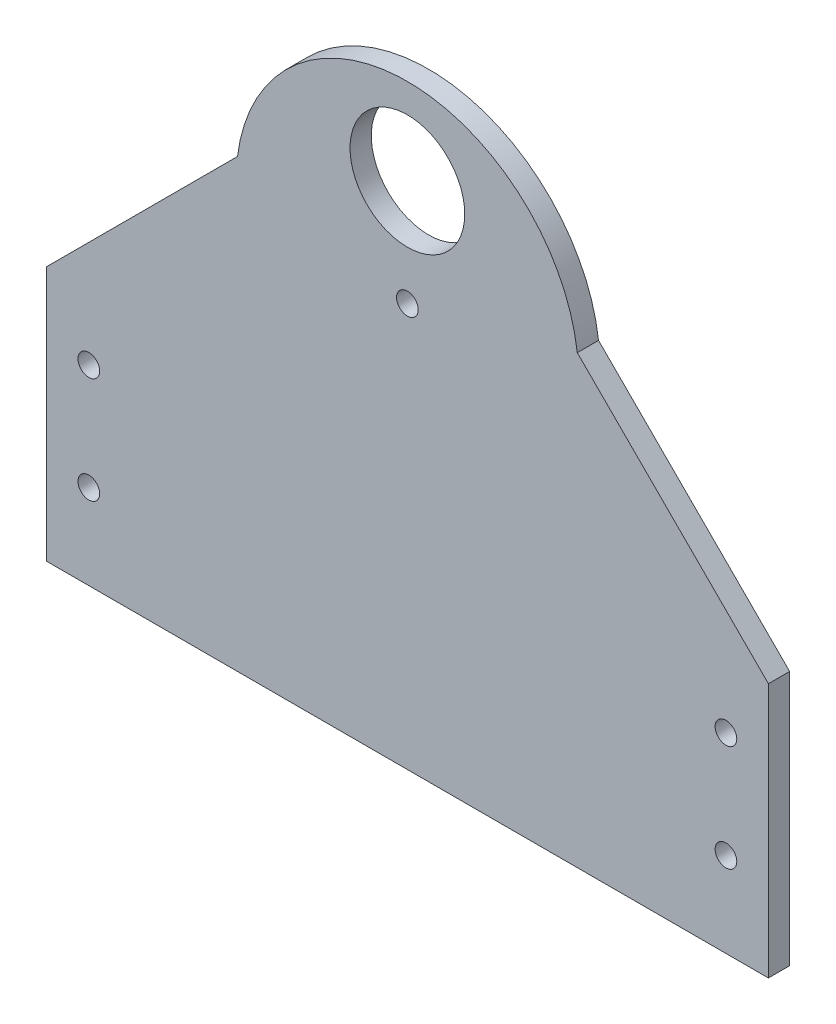
SolidWorks part; units mm, degrees
ref_plane "正面" through (0, 0, 0) normal (0, 0, 1) x (1, 0, 0)
ref_plane "平面" through (0, 0, 0) normal (0, 1, 0) x (1, 0, 0)
ref_plane "右側面" through (0, 0, 0) normal (1, 0, 0) x (0, 0, -1)
sketch "ｽｹｯﾁ1" plane through (0, 0, 0) normal (0, 0, 1) x (1, 0, 0)
  line L0 (-85, -71.4) -> (-85, -11.4)
  line L1 (-85, -11.4) -> (-40, 33.6)
  line L2 (-40, 33.6) -> (40, 33.6) construction
  line L3 (40, 33.6) -> (85, -11.4)
  line L4 (85, -11.4) -> (85, -71.4)
  line L5 (85, -71.4) -> (-85, -71.4)
  line L6 (40, 33.6) -> (-85, -71.4) construction
  line L7 (-40, 33.6) -> (85, -71.4) construction
  line L8 (0, 0) -> (0, -18.9) construction
  line L9 (-75, -61.4) -> (75, -61.4) construction
  line L10 (-75, -61.4) -> (-75, 23.6) construction
  line L11 (-75, 23.6) -> (75, 23.6) construction
  line L12 (75, -61.4) -> (75, 23.6) construction
  line L13 (-75, -61.4) -> (75, 23.6) construction
  line L14 (-75, 23.6) -> (75, -61.4) construction
  line L15 (0, 48.6) -> (0, 0) construction
  circle A0 centre (75, -26.4) radius 2.55
  circle A1 centre (75, -51.4) radius 2.55
  circle A2 centre (-75, -26.4) radius 2.55
  circle A3 centre (-75, -51.4) radius 2.55
  circle A4 centre (0, 23.6) radius 2.55
  arc A5 (-40, 33.6) -> (40, 33.6) centre (0, 28.6) cw
  circle A6 centre (0, 48.6) radius 13.5
  point P2 (0, 0)
  point P10 (0, -18.9)
  dimension "D9" = 20
  dimension "D13" = 5.1
  dimension "D14" = 5
  dimension "D15" = 27
  dimension "D1" = 170
  dimension "D2" = 45
  dimension "D3" = 45
  dimension "D4" = 80
  dimension "D5" = 60
  dimension "D6" = 10
  dimension "D7" = 10
  dimension "D8" = 10
  dimension "D10" = 25
  dimension "D11" = 20
  dimension "D12" = 25
  dimension "D16" = 15
extrude "ﾎﾞｽ - 押し出し1" add sketch "ｽｹｯﾁ1" along normal blind 5
